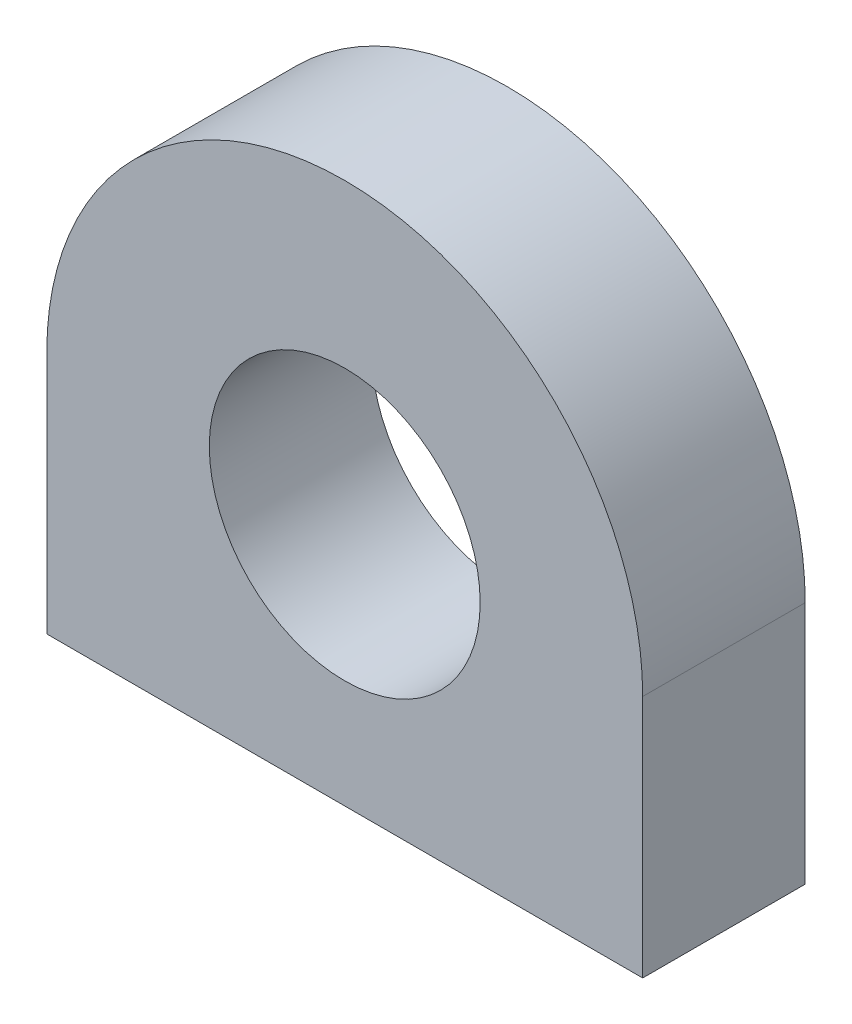
SolidWorks part; units mm, degrees
ref_plane "Front Plane" through (0, 0, 0) normal (0, 0, 1) x (1, 0, 0)
ref_plane "Top Plane" through (0, 0, 0) normal (0, 1, 0) x (1, 0, 0)
ref_plane "Right Plane" through (0, 0, 0) normal (1, 0, 0) x (0, 0, -1)
sketch "Sketch1" plane through (0, 0, 0) normal (0, 0, 1) x (1, 0, 0)
  line L0 (0, 0) -> (-110, 0)
  line L1 (-110, 0) -> (-110, 45)
  line L2 (0, 45) -> (0, 0)
  arc A0 (-110, 45) -> (0, 45) centre (-55, 45) cw
  circle A1 centre (-55, 45) radius 25
  point P6 (-55, 20)
  dimension "D2" = 45
  dimension "D3" = 50
  dimension "D1" = 110
extrude "Boss-Extrude1" add sketch "Sketch1" along normal blind 30
sketch "Sketch2" plane through (0, 0, 0) normal (0, 1, 0) x (1, 0, 0)
  line L0 (-55, 0) -> (-55, -30) construction
  line L1 (0, 0) -> (-110, 0) construction
  line L2 (-110, -30) -> (0, -30) construction
